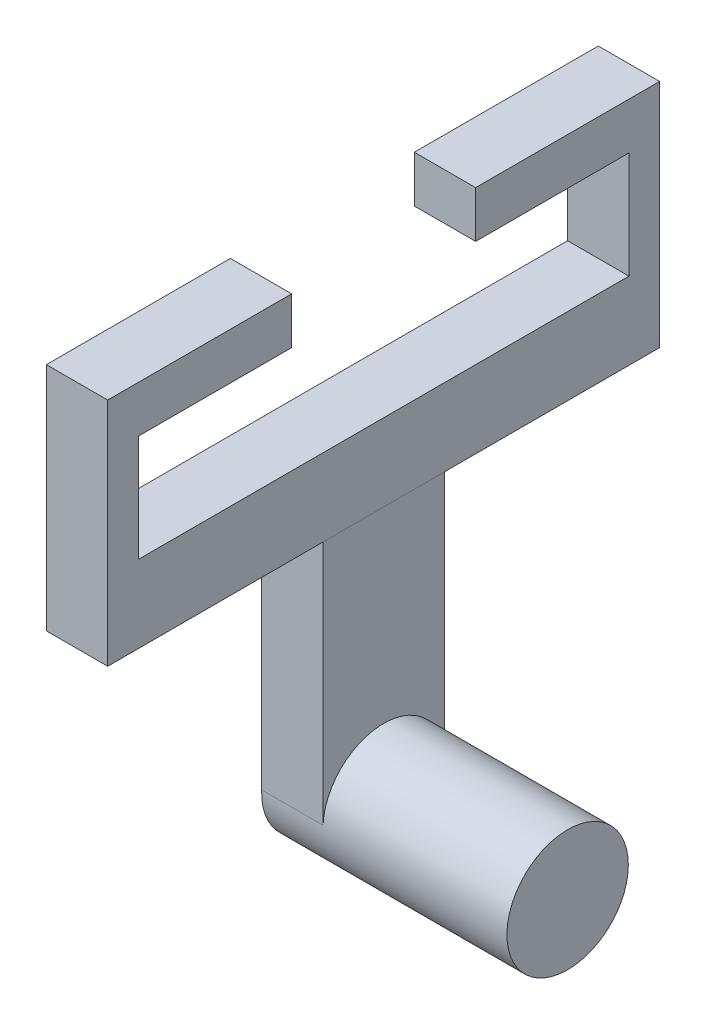
SolidWorks part; units mm, degrees
material "6061-T6 (SS)"
ref_plane "Front Plane" through (0, 0, 0) normal (0, 0, 1) x (1, 0, 0)
ref_plane "Top Plane" through (0, 0, 0) normal (0, 1, 0) x (1, 0, 0)
ref_plane "Right Plane" through (0, 0, 0) normal (1, 0, 0) x (0, 0, -1)
sketch "Sketch2" plane through (0, 0, 0) normal (1, 0, 0) x (0, 0, -1)
  circle A0 centre (0, 0) radius 12.573
  dimension "D1" = 25.146
extrude "Feature A" add sketch "Sketch2" along normal blind 50.8 contours A0
sketch "Sketch3" plane through (0, 0, 0) normal (-1, 0, 0) x (0, 0, 1)
  line L1 (-12.5585, 0.6026) -> (12.5875, 0.6026)
  line L2 (-12.5585, 0.6026) -> (-12.5585, 51.4026)
  line L3 (-12.5585, 51.4026) -> (12.5875, 51.4026)
  line L4 (12.5875, 0.6026) -> (12.5875, 51.4026)
  circle A0 centre (0, 0) radius 12.573 construction
  dimension "D1" = 25.146
  dimension "D2" = 50.8
extrude "Feature B" add sketch "Sketch3" against normal blind 12.7
sketch "Sketch5" plane through (0, 0, 0) normal (1, 0, 0) x (0, 0, -1)
  line L1 (50.8, 67.3933) -> (-50.8, 67.3933)
  line L2 (50.8, 67.3933) -> (50.8, 51.3913)
  line L3 (50.8, 51.3913) -> (-50.8, 51.3913)
  line L4 (-50.8, 67.3933) -> (-50.8, 51.3913)
  line L5 (50.8, 67.3933) -> (-50.8, 51.3913) construction
  line L6 (50.8, 51.3913) -> (-50.8, 67.3933) construction
  point P0 (0, 59.3923)
  dimension "D1" = 101.6
  dimension "D2" = 16.002
extrude "Feature C" add sketch "Sketch5" along normal blind 12.7 separate body
sketch "Sketch10" plane through (12.7, 0, 0) normal (1, 0, 0) x (0, 0, -1)
  line L1 (-50.8, 51.3913) -> (-57.15, 51.3913)
  line L2 (-50.8, 51.3913) -> (-50.8, 89.4913)
  line L3 (-50.8, 89.4913) -> (-57.15, 89.4913)
  line L4 (-57.15, 51.3913) -> (-57.15, 89.4913)
  line L5 (50.8, 51.3913) -> (57.15, 51.3913)
  line L6 (50.8, 51.3913) -> (50.8, 89.4913)
  line L7 (50.8, 89.4913) -> (57.15, 89.4913)
  line L8 (57.15, 51.3913) -> (57.15, 89.4913)
  dimension "D1" = 38.1
  dimension "D2" = 38.1
  dimension "D3" = 6.35
  dimension "D4" = 6.35
extrude "Feature D" add sketch "Sketch10" against normal through all
sketch "Sketch11" plane through (12.7, 0, 0) normal (1, 0, 0) x (0, 0, -1)
  line L1 (-57.15, 89.4913) -> (-19.05, 89.4913)
  line L2 (-57.15, 89.4913) -> (-57.15, 99.1433)
  line L3 (-57.15, 99.1433) -> (-19.05, 99.1433)
  line L4 (-19.05, 89.4913) -> (-19.05, 99.1433)
  line L5 (57.15, 89.4913) -> (19.05, 89.4913)
  line L6 (57.15, 89.4913) -> (57.15, 99.1433)
  line L7 (57.15, 99.1433) -> (19.05, 99.1433)
  line L8 (19.05, 89.4913) -> (19.05, 99.1433)
  dimension "D1" = 38.1
  dimension "D2" = 38.1
  dimension "D3" = 9.652
  dimension "D4" = 9.652
extrude "Feature E" add sketch "Sketch11" against normal through all
equation "\"D_A\"= ( ( 8 * \"SF\" * \"F\" * \"L_A\" ^ 3 ) / ( \"E\" * pi * \"def\" ) ) ^ ( 1 / 4 )'Required A diameter"
equation "\"t_B\"= 0.50in'Feature B thickness/ Extrusion"
equation "\"h_B\"= 2.00in'Feature B Height "
equation "\"h_C\"= 0.625in'Feature C height"
equation "\"L_C\"= 4.00in'Feature C length"
equation "\"L_D\"= 1.500in'Feature D length"
equation "\"h_E\"= 0.375in'Feature E height"
equation "\"L_E\"= 1.500in'Feature E length"
equation "\"W_B\"= \"D_A\"'Feature B width"
equation "\"L_A\"= 2.00in'Feature A Length"
equation "\"t_C\"= \"t_B\"'Feature C thickness/ extrusion"
equation "\"t_D\"= \"t_B\"'Feature D thickness/ extrusion"
equation "\"t_E\"= \"t_B\"'Fetaure E thickness/ extrusion"
equation "\"F\"= 600'Total force applied"
equation "\"P\"= 300'Symmetric half-load"
equation "\"SF\"= 4'Safety Factor"
equation "\"Sy\"= 40000'Yield strength"
equation "\"E\"= 10000000'Modulus of elasticiy"
equation "\"def\"= 0.005in'deflection"
equation "\"H_D\"= 1.50 - \"h_C\"'Height of Feature D"
equation "\"W_D\"= 0.25in"
